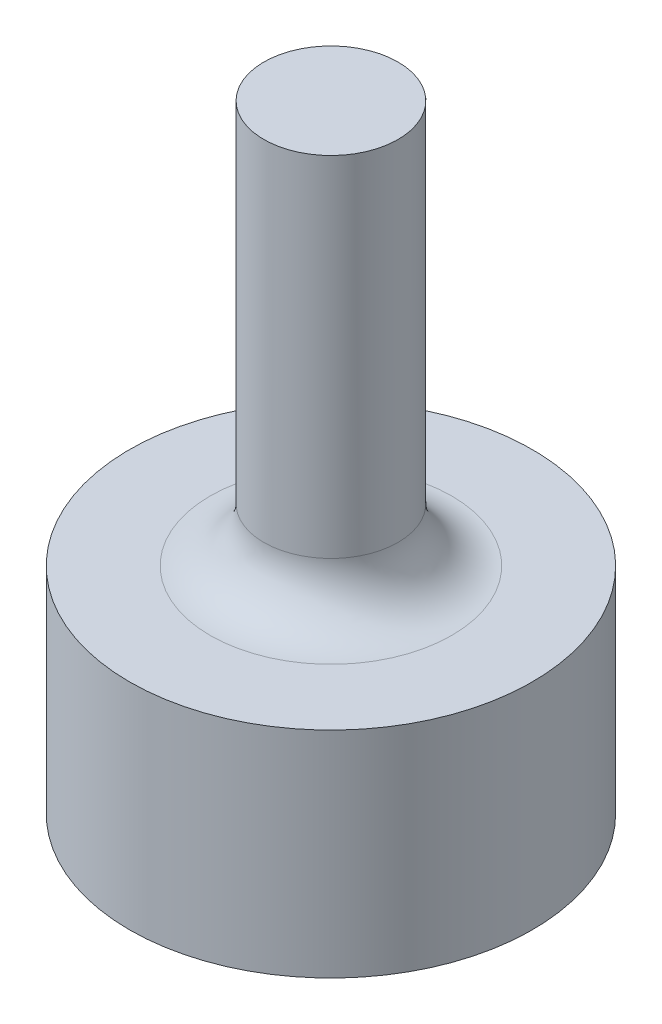
SolidWorks part; units mm, degrees
ref_plane "Front Plane" through (0, 0, 0) normal (0, 0, 1) x (1, 0, 0)
ref_plane "Top Plane" through (0, 0, 0) normal (0, 1, 0) x (1, 0, 0)
ref_plane "Right Plane" through (0, 0, 0) normal (1, 0, 0) x (0, 0, -1)
sketch "Sketch1" plane through (0, 0, 0) normal (0, 1, 0) x (1, 0, 0)
  circle A0 centre (0, 0) radius 9.525
extrude "Boss-Extrude1" add sketch "Sketch1" along normal blind 10.16 contours A0
sketch "Sketch2" plane through (0, 0, 0) normal (0, -1, 0) x (-1, 0, 0)
  circle A0 centre (0, 0) radius 7.9375
extrude "Cut-Extrude1" cut sketch "Sketch2" against normal blind 3.175
sketch "Sketch3" plane through (0, 10.16, 0) normal (0, 1, 0) x (1, 0, 0)
  circle A0 centre (0, 0) radius 3.175
extrude "Boss-Extrude2" add sketch "Sketch3" along normal blind 19.05
fillet "Fillet1" radius 2.54 1 edges at (0, 10.16, 3.175)
